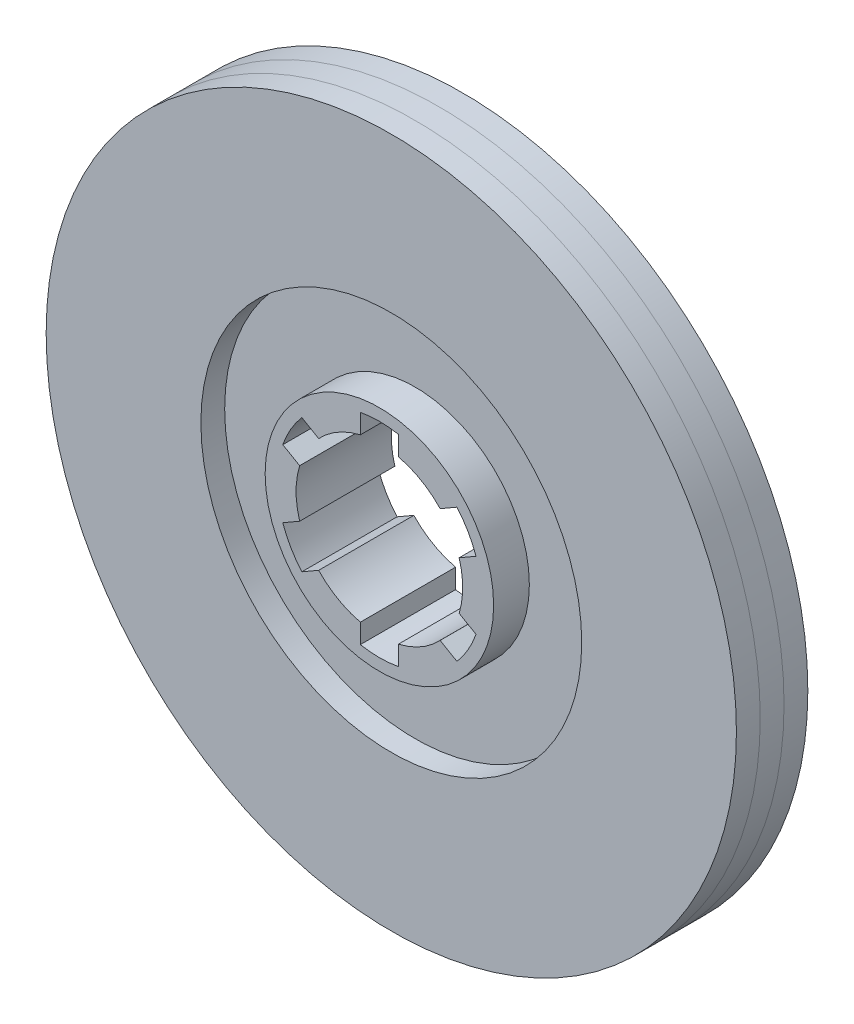
SolidWorks part; units mm, degrees
material "Alloy Steel"
material "Cast Carbon Steel"
ref_plane "Front Plane" through (0, 0, 0) normal (0, 0, 1) x (1, 0, 0)
ref_plane "Top Plane" through (0, 0, 0) normal (0, 1, 0) x (1, 0, 0)
ref_plane "Right Plane" through (0, 0, 0) normal (1, 0, 0) x (0, 0, -1)
sketch "Sketch1" plane through (0, 0, 0) normal (0, 0, 1) x (1, 0, 0)
  circle A0 centre (0, 0) radius 72.5
  dimension "D1" = 145
extrude "Boss-Extrude1" add sketch "Sketch1" along normal mid plane 5
sketch "Sketch3" plane through (0, 0, 0) normal (0, 0, 1) x (1, 0, 0)
  circle A0 centre (0, 0) radius 24
  dimension "D1" = 48
extrude "Boss-Extrude2" add sketch "Sketch3" along normal mid plane 20
sketch "Sketch4" plane through (0, 0, 2.5) normal (0, 0, 1) x (1, 0, 0)
  circle A0 centre (0, 0) radius 72.5 construction
  circle A1 centre (0, 0) radius 72.5
  circle A2 centre (0, 0) radius 40
  dimension "D1" = 80
extrude "Boss-Extrude3" add sketch "Sketch4" along normal blind 5 separate body
mirror "Mirror3" about plane through (0, 0, 0) normal (0, 0, 1) of bodies 103
sketch "Sketch5" plane through (0, 0, 10) normal (0, 0, 1) x (1, 0, 0)
  line L0 (0, 0) -> (0, 17.5) construction
  line L1 (-4, 21.1246) -> (-4, 17.0367)
  line L2 (4, 21.1246) -> (4, 17.0367)
  line L3 (16.2945, 14.0264) -> (12.7542, 11.9825)
  line L4 (20.2945, 7.0982) -> (16.7542, 5.0543)
  line L5 (20.2945, -7.0982) -> (16.7542, -5.0543)
  line L6 (16.2945, -14.0264) -> (12.7542, -11.9825)
  line L7 (4, -21.1246) -> (4, -17.0367)
  line L8 (-4, -21.1246) -> (-4, -17.0367)
  line L9 (-16.2945, -14.0264) -> (-12.7542, -11.9825)
  line L10 (-20.2945, -7.0982) -> (-16.7542, -5.0543)
  line L11 (-20.2945, 7.0982) -> (-16.7542, 5.0543)
  line L12 (-16.2945, 14.0264) -> (-12.7542, 11.9825)
  arc A0 (-12.7542, -11.9825) -> (-4, -17.0367) centre (0, 0) ccw
  arc A1 (-16.2945, 14.0264) -> (-20.2945, 7.0982) centre (0, 0) ccw
  arc A2 (-20.2945, -7.0982) -> (-16.2945, -14.0264) centre (0, 0) ccw
  arc A3 (4, 21.1246) -> (-4, 21.1246) centre (0, 0) ccw
  arc A4 (20.2945, 7.0982) -> (16.2945, 14.0264) centre (0, 0) ccw
  arc A5 (16.2945, -14.0264) -> (20.2945, -7.0982) centre (0, 0) ccw
  arc A6 (-4, -21.1246) -> (4, -21.1246) centre (0, 0) ccw
  arc A7 (-16.7542, 5.0543) -> (-16.7542, -5.0543) centre (0, 0) ccw
  arc A8 (-4, 17.0367) -> (-12.7542, 11.9825) centre (0, 0) ccw
  arc A9 (12.7542, 11.9825) -> (0, 17.5) centre (0, 0) ccw
  arc A10 (16.7542, -5.0543) -> (16.7542, 5.0543) centre (0, 0) ccw
  arc A11 (4, -17.0367) -> (12.7542, -11.9825) centre (0, 0) ccw
  point P31 (0, 0)
  dimension "D1" = 35
  dimension "D2" = 43
  dimension "D3" = 8
  dimension "D4" = 4
  dimension "D5" = 6
extrude "Cut-Extrude1" cut sketch "Sketch5" against normal through all
